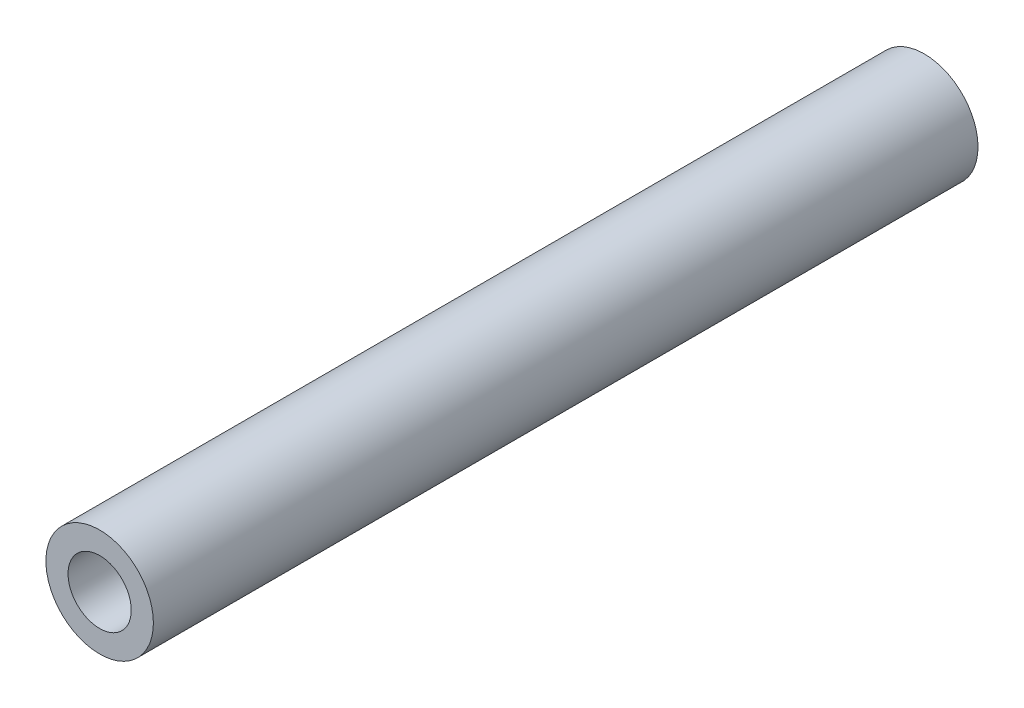
SolidWorks part; units mm, degrees
ref_plane "Front Plane" through (0, 0, 0) normal (0, 0, 1) x (1, 0, 0)
ref_plane "Top Plane" through (0, 0, 0) normal (0, 1, 0) x (1, 0, 0)
ref_plane "Right Plane" through (0, 0, 0) normal (1, 0, 0) x (0, 0, -1)
sketch "Sketch1" plane through (0, 0, 0) normal (0, 0, 1) x (1, 0, 0)
  circle A0 centre (0, 0) radius 2.3
  circle A1 centre (0, 0) radius 3.91
extrude "Boss-Extrude1" add sketch "Sketch1" along normal blind 60
